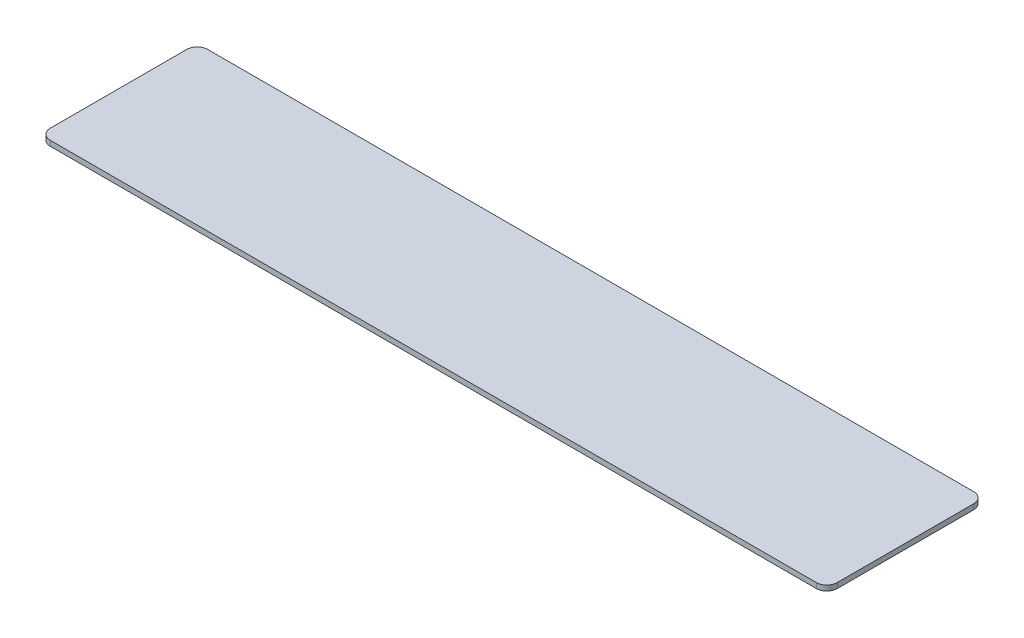
SolidWorks part; units mm, degrees
material "Thornel Mat VMA"
ref_plane "Front Plane" through (0, 0, 0) normal (0, 0, 1) x (1, 0, 0)
ref_plane "Top Plane" through (0, 0, 0) normal (0, 1, 0) x (1, 0, 0)
ref_plane "Right Plane" through (0, 0, 0) normal (1, 0, 0) x (0, 0, -1)
sketch "Sketch1" plane through (0, 0, 0) normal (0, 1, 0) x (1, 0, 0)
  line L1 (0, 0) -> (190.5, 0)
  line L2 (0, 0) -> (0, 38.1)
  line L3 (0, 38.1) -> (190.5, 38.1)
  line L4 (190.5, 0) -> (190.5, 38.1)
  dimension "D1" = 38.1
  dimension "D2" = 190.5
extrude "Boss-Extrude1" add sketch "Sketch1" along normal blind 1.27
fillet "Fillet1" radius 2.54 4 edges at (190.5, 0.635, 0) (190.5, 0.635, -38.1) (0, 0.635, -38.1) (0, 0.635, 0)
